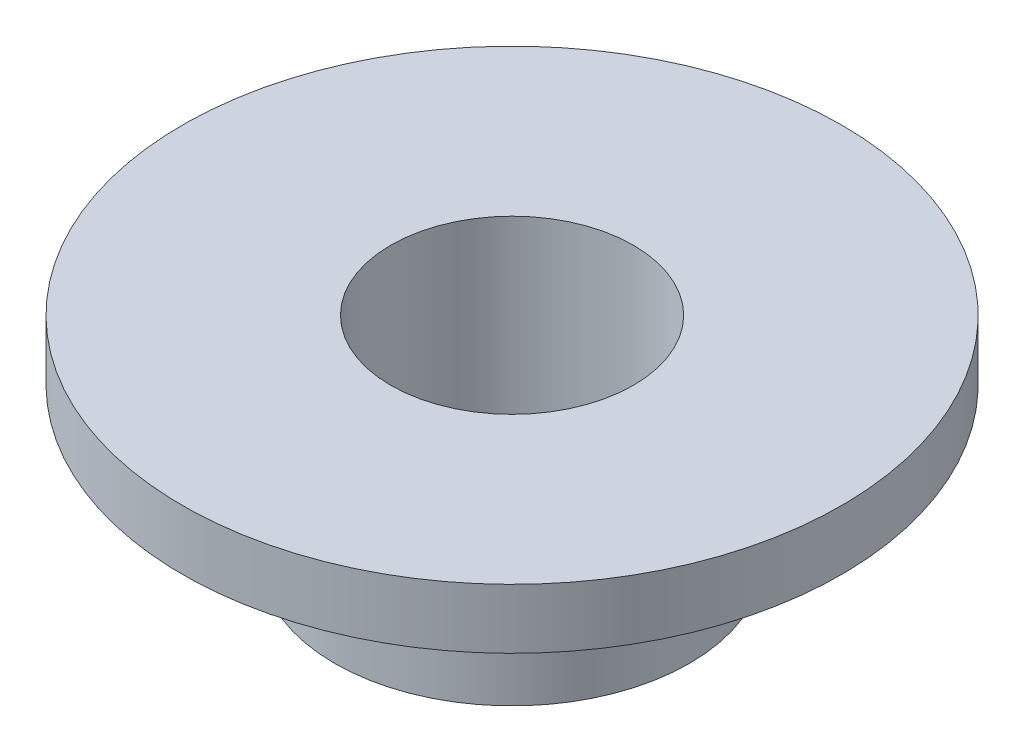
SolidWorks part; units mm, degrees
ref_plane "Plan de face" through (0, 0, 0) normal (0, 0, 1) x (1, 0, 0)
ref_plane "Plan de dessus" through (0, 0, 0) normal (0, 1, 0) x (1, 0, 0)
ref_plane "Plan de droite" through (0, 0, 0) normal (1, 0, 0) x (0, 0, -1)
ref_plane "Plan1" through (0, 0, 10.4) normal (0, 0, 1) x (1, 0, 0)
sketch "Esquisse1" plane through (0, 0, 10.4) normal (0, 0, 1) x (1, 0, 0)
  line L0 (41.3578, -27.6371) -> (41.3578, -23.5371)
  line L1 (41.3578, -23.5371) -> (45.4328, -23.5371)
  line L2 (45.4328, -23.5371) -> (45.4328, -21.9371)
  line L3 (45.4328, -21.9371) -> (39.8578, -21.9371)
  line L4 (39.8578, -21.9371) -> (39.8578, -27.6371)
  line L5 (39.8578, -27.6371) -> (41.3578, -27.6371)
  line L6 (36.6078, -21.9371) -> (36.6078, -27.9371) construction
  dimension "D1" = 17.65
  dimension "D2" = 1.6
  dimension "D3" = 5.7
  dimension "D4" = 9.5
  dimension "D5" = 6.5
revolve "Révolution1" add sketch "Esquisse1" angle 360 about L6
